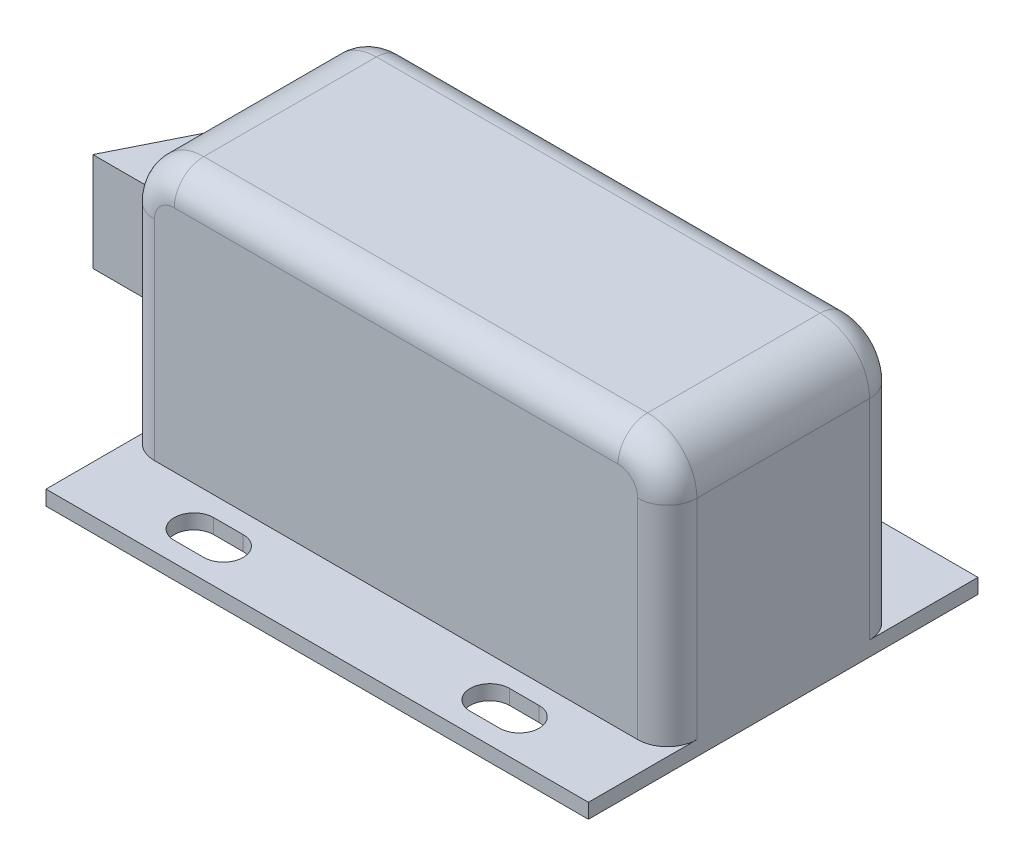
SolidWorks part; units mm, degrees
ref_plane "Front Plane" through (0, 0, 0) normal (0, 0, 1) x (1, 0, 0)
ref_plane "Top Plane" through (0, 0, 0) normal (0, 1, 0) x (1, 0, 0)
ref_plane "Right Plane" through (0, 0, 0) normal (1, 0, 0) x (0, 0, -1)
ref_plane "Plane1" through (0, 13.85, 0) normal (0, 1, 0) x (1, 0, 0)
sketch "Sketch1" plane through (0, 13.85, 0) normal (0, 1, 0) x (1, 0, 0)
  line L0 (-27.5, 8) -> (-27.5, -31.5)
  line L1 (-27.5, -31.5) -> (27.5, -31.5)
  line L2 (27.5, -31.5) -> (27.5, 8)
  line L3 (27.5, 8) -> (-27.5, 8)
extrude "Boss-Extrude1" add sketch "Sketch1" against normal blind 27.7
sketch "Sketch2" plane through (-27.5, 0, 0) normal (-1, 0, 0) x (0, 0, 1)
  line L0 (31.5, 13.85) -> (23.5, 13.85)
  line L1 (23.5, 13.85) -> (23.5, -12.35)
  line L2 (23.5, -12.35) -> (31.5, -12.35)
  line L3 (31.5, -12.35) -> (31.5, 13.85)
extrude "Cut-Extrude1" cut sketch "Sketch2" against normal through all
sketch "Sketch3" plane through (-27.5, 0, 0) normal (-1, 0, 0) x (0, 0, 1)
  line L0 (0, -12.35) -> (0, 13.85)
  line L1 (0, 13.85) -> (-8, 13.85)
  line L2 (-8, 13.85) -> (-8, -12.35)
  line L3 (-8, -12.35) -> (0, -12.35)
extrude "Cut-Extrude2" cut sketch "Sketch3" against normal through all
sketch "Sketch4" plane through (0, -12.35, 0) normal (0, 1, 0) x (-1, 0, 0)
  line L0 (-13.5, -2) -> (-16.5, -2)
  line L1 (-16.5, -6) -> (-13.5, -6)
  arc A0 (-16.5, -2) -> (-16.5, -6) centre (-16.5, -4) ccw
  arc A1 (-13.5, -6) -> (-13.5, -2) centre (-13.5, -4) ccw
extrude "Cut-Extrude3" cut sketch "Sketch4" against normal through all
sketch "Sketch5" plane through (0, -13.85, 0) normal (0, -1, 0) x (1, 0, 0)
  line L0 (-16.5, -6) -> (-13.5, -6)
  line L1 (-13.5, -2) -> (-16.5, -2)
  arc A0 (-13.5, -6) -> (-13.5, -2) centre (-13.5, -4) ccw
  arc A1 (-16.5, -2) -> (-16.5, -6) centre (-16.5, -4) ccw
extrude "Cut-Extrude4" cut sketch "Sketch5" against normal through all
sketch "Sketch6" plane through (0, -12.35, 0) normal (0, 1, 0) x (-1, 0, 0)
  line L0 (16.5, 29.5) -> (13.5, 29.5)
  line L1 (13.5, 25.5) -> (16.5, 25.5)
  arc A0 (13.5, 29.5) -> (13.5, 25.5) centre (13.5, 27.5) ccw
  arc A1 (16.5, 25.5) -> (16.5, 29.5) centre (16.5, 27.5) ccw
extrude "Cut-Extrude5" cut sketch "Sketch6" against normal through all
sketch "Sketch7" plane through (0, -13.85, 0) normal (0, -1, 0) x (1, 0, 0)
  line L0 (13.5, 25.5) -> (16.5, 25.5)
  line L1 (16.5, 29.5) -> (13.5, 29.5)
  arc A0 (16.5, 25.5) -> (16.5, 29.5) centre (16.5, 27.5) ccw
  arc A1 (13.5, 29.5) -> (13.5, 25.5) centre (13.5, 27.5) ccw
extrude "Cut-Extrude6" cut sketch "Sketch7" against normal through all
ref_plane "Plane2" through (0, -5.35, 0) normal (0, -1, 0) x (1, 0, 0)
sketch "Sketch8" plane through (0, -5.35, 0) normal (0, -1, 0) x (1, 0, 0)
  line L0 (-37.5, 16.75) -> (-32.5, 6.75)
  line L1 (-32.5, 6.75) -> (-27.5, 6.75)
  line L2 (-27.5, 6.75) -> (-27.5, 16.75)
  line L3 (-27.5, 16.75) -> (-37.5, 16.75)
extrude "Boss-Extrude2" add sketch "Sketch8" against normal blind 10
fillet "Fillet1" radius 5 2 edges at (27.5, 13.85, 11.75) (-27.5, 13.85, 11.75)
fillet "Fillet2" radius 3 10 edges at (27.5, -1.75, 23.5) (26.0355, 12.3855, 23.5) (0, 13.85, 23.5) (-26.0355, 12.3855, 23.5) (-27.5, -1.75, 23.5) (-27.5, -1.75, 0) (-26.0355, 12.3855, 0) (0, 13.85, 0) (26.0355, 12.3855, 0) (27.5, -1.75, 0)
